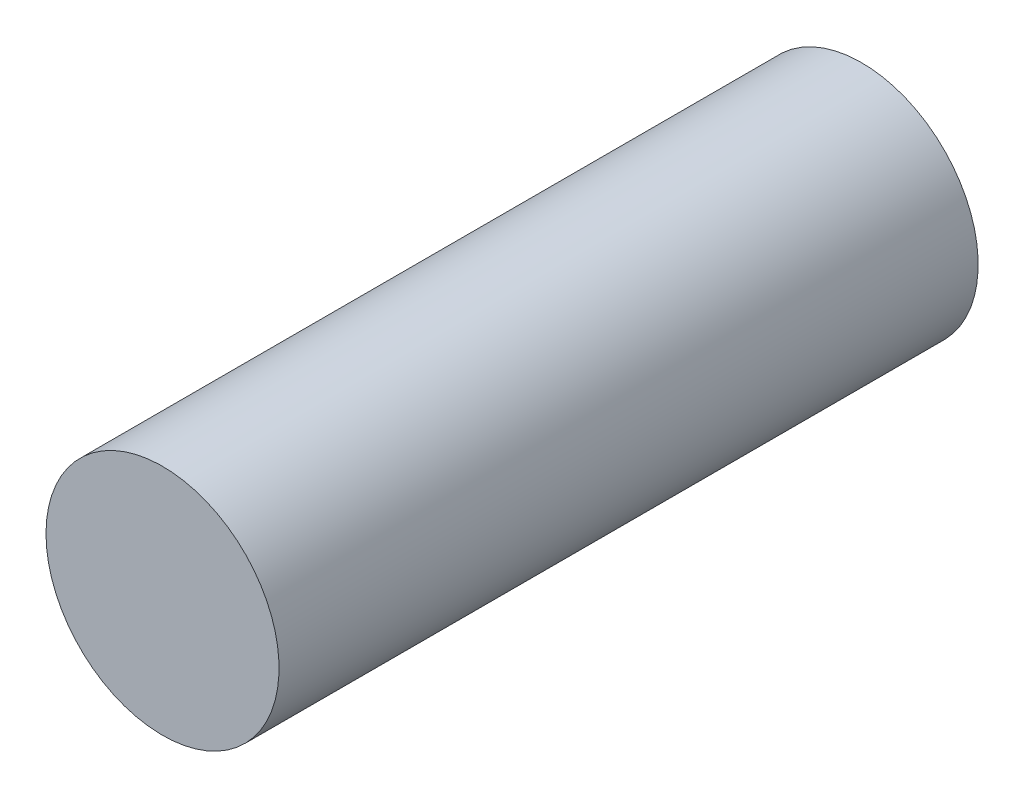
SolidWorks part; units mm, degrees
material "6061 Alloy"
ref_plane "Front Plane" through (0, 0, 0) normal (0, 0, 1) x (1, 0, 0)
ref_plane "Top Plane" through (0, 0, 0) normal (0, 1, 0) x (1, 0, 0)
ref_plane "Right Plane" through (0, 0, 0) normal (1, 0, 0) x (0, 0, -1)
sketch "Sketch1" plane through (0, 0, 0) normal (0, 0, 1) x (1, 0, 0)
  circle A0 centre (0, 0) radius 6.35
  dimension "D1" = 12.7
extrude "Boss-Extrude1" add sketch "Sketch1" along normal blind 38.1
